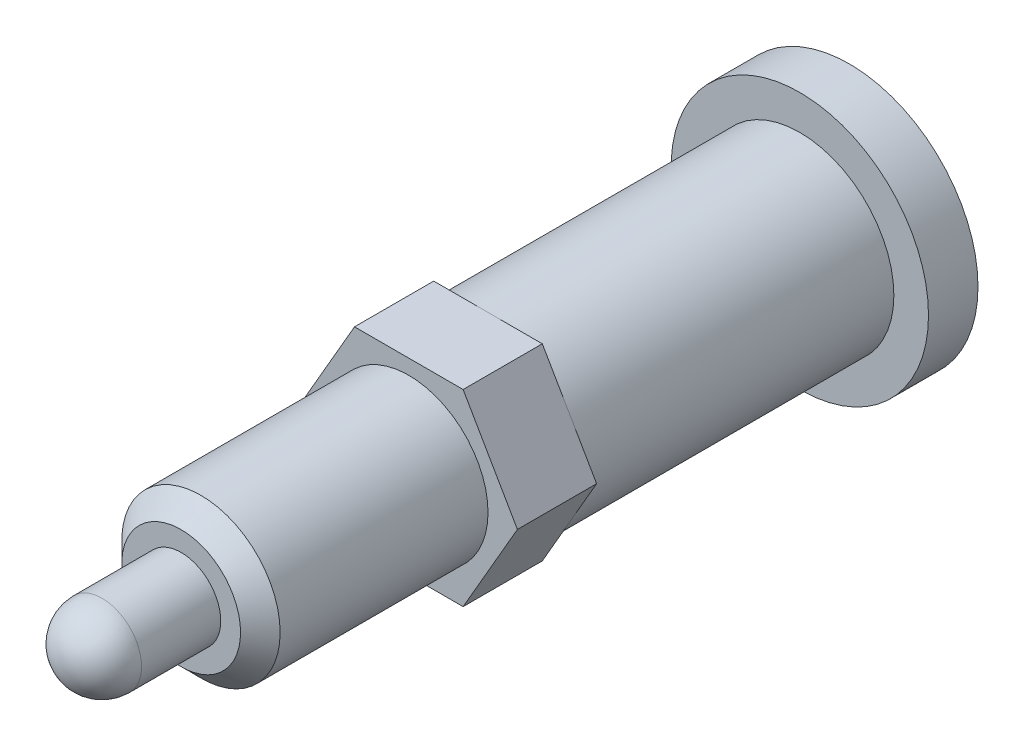
SolidWorks part; units mm, degrees
material "Q235A焊接件"
ref_plane "前视" through (0, 0, 0) normal (0, 0, 1) x (1, 0, 0)
ref_plane "上视" through (0, 0, 0) normal (0, 1, 0) x (1, 0, 0)
ref_plane "右视" through (0, 0, 0) normal (1, 0, 0) x (0, 0, -1)
sketch "草图1" plane through (0, 0, 0) normal (0, 1, 0) x (1, 0, 0)
  line L0 (0, 0) -> (0, 100.7595) construction
  line L1 (0, -50) -> (0, 50) construction
  line L2 (4, 0) -> (4, 8)
  line L3 (4, 8) -> (8, 8)
  line L4 (8, 8) -> (8, 31)
  line L5 (8, 31) -> (9.5, 31)
  line L6 (9.5, 31) -> (9.5, 70.5)
  line L7 (9.5, 70.5) -> (13, 70.5)
  line L8 (13, 70.5) -> (13, 75.5)
  line L9 (0, -4) -> (21.9138, -4) construction
  line L10 (0, 76.5) -> (26.6642, 76.5) construction
  line L11 (0, -4) -> (0, 76.5)
  arc A0 (0, -4) -> (4, 0) centre (0, 0) ccw
  arc A1 (13, 75.5) -> (0, 76.5) centre (0, -8.5) ccw
  dimension "D1" = 8
  dimension "D2" = 8
  dimension "D3" = 12
  dimension "D4" = 23
  dimension "D5" = 13
  dimension "D6" = 9.5
  dimension "D8" = 80.5
  dimension "D9" = 5
  dimension "D10" = 2
revolve "旋转1" add sketch "草图1" angle 360 about L0
cosmetic thread "装饰螺纹线1" parameters "D2"=14
sketch "草图2" plane through (0, 0, -31) normal (0, 0, 1) x (1, 0, 0)
  line L1 (10.9697, 0) -> (5.4848, 9.5)
  line L2 (5.4848, 9.5) -> (-5.4848, 9.5)
  line L3 (-5.4848, 9.5) -> (-10.9697, 0)
  line L4 (-10.9697, 0) -> (-5.4848, -9.5)
  line L5 (-5.4848, -9.5) -> (5.4848, -9.5)
  line L6 (5.4848, -9.5) -> (10.9697, 0)
  circle A0 centre (0, 0) radius 9.5 construction
  dimension "D1" = 19
extrude "凸台-拉伸1" add sketch "草图2" against normal blind 8
chamfer "倒角1" distance 2 angle 45 1 edges at (8, 0, -8)
